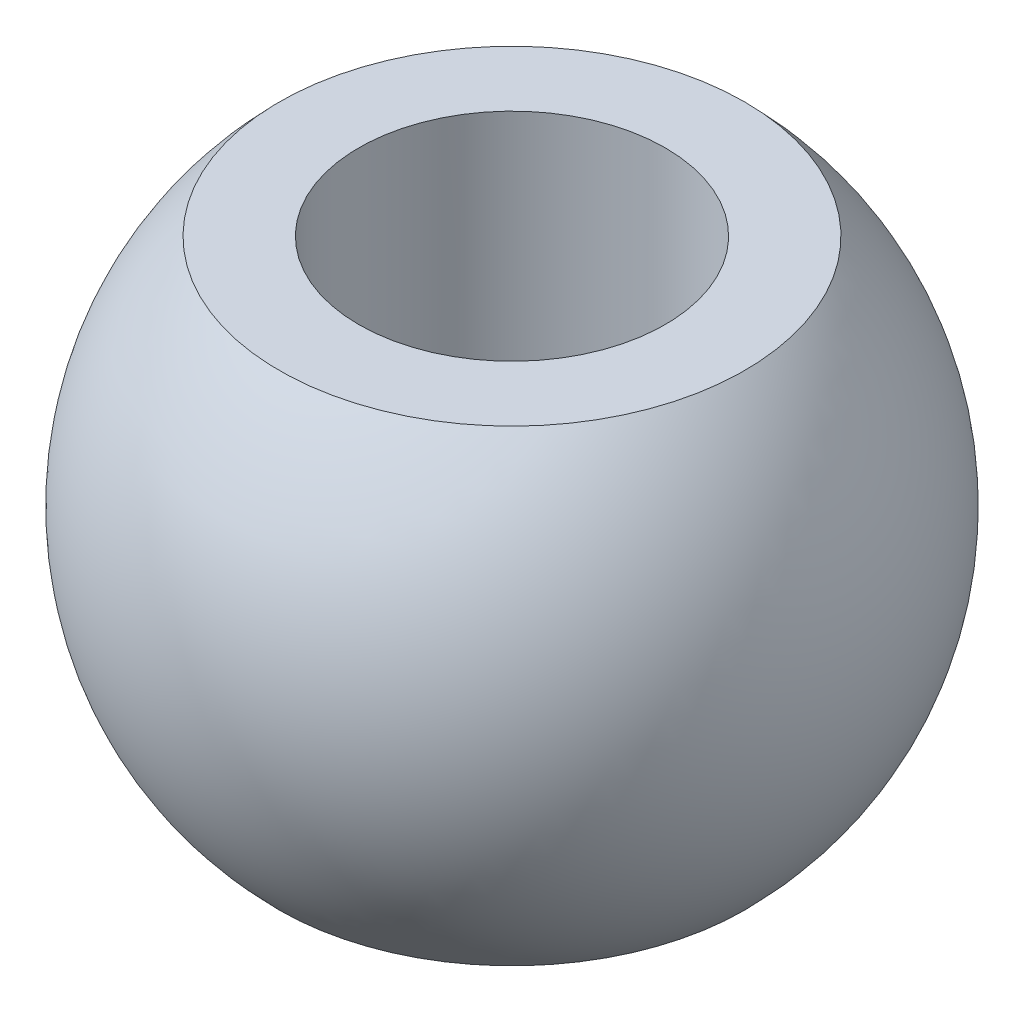
SolidWorks part; units mm, degrees
ref_plane "Спереди" through (0, 0, 0) normal (0, 0, 1) x (1, 0, 0)
ref_plane "Сверху" through (0, 0, 0) normal (0, 1, 0) x (1, 0, 0)
ref_plane "Справа" through (0, 0, 0) normal (1, 0, 0) x (0, 0, -1)
sketch "Эскиз1" plane through (0, 0, 0) normal (0, 1, 0) x (1, 0, 0)
  line L0 (0, 6.35) -> (0, -6.35) construction
  line L1 (0, 6.35) -> (0, -6.35)
  arc A0 (0, -6.35) -> (0, 6.35) centre (0, 0) ccw
  dimension "D1" = 12.7
revolve "Повернуть3" add sketch "Эскиз1" angle 360 about L0
sketch "Эскиз2" plane through (0, 0, 0) normal (0, 1, 0) x (1, 0, 0)
  circle A0 centre (0, 0) radius 2.95
  dimension "D1" = 5.9
extrude "Вырез-Вытянуть1" cut sketch "Эскиз2" against normal through all both and the other way through all
sketch "Эскиз3" plane through (0, 0, 0) normal (0, 0, 1) x (1, 0, 0)
  line L0 (-4.4802, 4.5) -> (4.4802, 4.5)
  line L1 (-6.35, 0) -> (6.35, 0) construction
  line L2 (-4.4802, -4.5) -> (4.4802, -4.5)
  arc A0 (-4.4802, -4.5) -> (4.4802, -4.5) centre (0, 0) ccw
  arc A1 (-2.95, 5.6232) -> (-2.95, -5.6232) centre (0, 0) ccw construction
  arc A2 (-4.4802, 4.5) -> (-6.35, 0) centre (0, 0) ccw construction
  arc A3 (-6.35, 0) -> (-4.4802, -4.5) centre (0, 0) ccw construction
  arc A4 (4.4802, 4.5) -> (-4.4802, 4.5) centre (0, 0) ccw
  arc A5 (6.35, 0) -> (4.4802, 4.5) centre (0, 0) ccw construction
  arc A6 (4.4802, -4.5) -> (6.35, 0) centre (0, 0) ccw construction
  dimension "D1" = 9
extrude "Вырез-Вытянуть2" cut sketch "Эскиз3" against normal through all both and the other way through all
equation "\"Ball_bearing_D\"= 12.7"
equation "\"Ball_bearing_h1\"= 9"
equation "\"Ball_bearing_d1\"= 5.9"
equation "\"Ball_bearing_d2\"= 18"
equation "\"Ball_bearing_h2\"= 6.6"
equation "\"Brake_tube_d1\"= 2"
equation "\"Brake_tube_d2\"= 5"
equation "\"Brake_tube_h\"= 20"
equation "\"D1@Эскиз1\"=\"Ball_bearing_D\""
equation "\"D1@Эскиз2\"=\"Ball_bearing_d1\""
equation "\"D1@Эскиз3\"=\"Ball_bearing_h1\""
